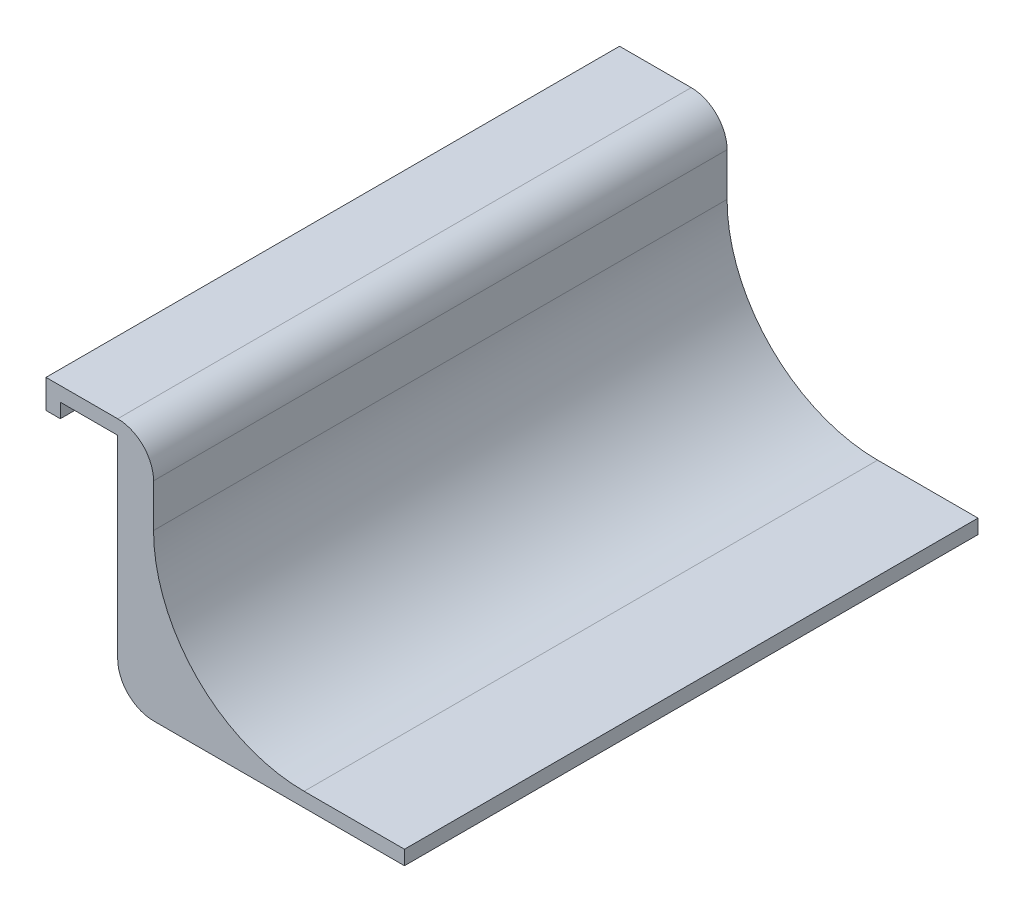
SolidWorks part; units mm, degrees
ref_plane "Front Plane" through (0, 0, 0) normal (0, 0, 1) x (1, 0, 0)
ref_plane "Top Plane" through (0, 0, 0) normal (0, 1, 0) x (1, 0, 0)
ref_plane "Right Plane" through (0, 0, 0) normal (1, 0, 0) x (0, 0, -1)
sketch "Sketch1" plane through (0, 0, 0) normal (0, 1, 0) x (1, 0, 0)
  line L1 (20, 40) -> (-20, 40)
  line L2 (20, 40) -> (20, -40)
  line L3 (20, -40) -> (-20, -40)
  line L4 (-20, 40) -> (-20, -40)
  line L5 (20, 40) -> (-20, -40) construction
  line L6 (20, -40) -> (-20, 40) construction
  point P0 (0, 0)
  dimension "D1" = 40
  dimension "D2" = 80
extrude "Boss-Extrude4" add sketch "Sketch1" along normal blind 2
sketch "Sketch4" plane through (0, 2, 0) normal (0, 1, 0) x (1, 0, 0)
  line L0 (-20, -40) -> (20, -40) construction
  line L1 (-20, 40) -> (-15, 40)
  line L2 (-20, 40) -> (-20, -40)
  line L3 (-20, -40) -> (-15, -40)
  line L4 (-15, 40) -> (-15, -40)
  dimension "D1" = 5
extrude "Boss-Extrude5" add sketch "Sketch4" along normal blind 32
fillet "Fillet3" radius 21 1 edges at (-15, 2, 0)
sketch "Sketch5" plane through (-20, 0, 0) normal (-1, 0, 0) x (0, 0, 1)
  line L0 (40, 34) -> (40, 0) construction
  line L1 (-40, 34) -> (40, 34)
  line L2 (-40, 34) -> (-40, 32)
  line L3 (-40, 32) -> (40, 32)
  line L4 (40, 34) -> (40, 32)
  dimension "D1" = 2
extrude "Boss-Extrude6" add sketch "Sketch5" along normal blind 10
sketch "Sketch6" plane through (0, 32, 0) normal (0, -1, 0) x (1, 0, 0)
  line L0 (-30, 40) -> (-20, 40) construction
  line L1 (-30, -40) -> (-28, -40)
  line L2 (-30, -40) -> (-30, 40)
  line L3 (-30, 40) -> (-28, 40)
  line L4 (-28, -40) -> (-28, 40)
  dimension "D1" = 2
extrude "Boss-Extrude7" add sketch "Sketch6" along normal blind 2
fillet "Fillet4" radius 5 2 edges at (-20, 0, 0) (-15, 34, 0)
